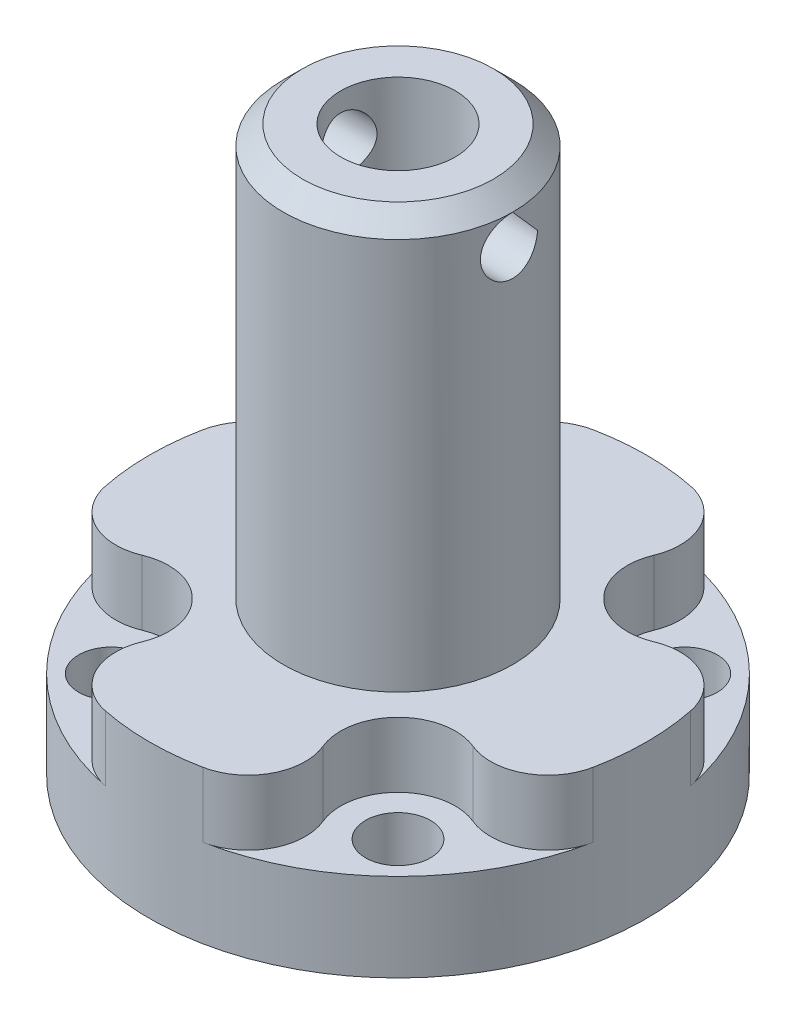
SolidWorks part; units mm, degrees
material "6061 Alloy"
ref_plane "Front Plane" through (0, 0, 0) normal (0, 0, 1) x (1, 0, 0)
ref_plane "Top Plane" through (0, 0, 0) normal (0, 1, 0) x (1, 0, 0)
ref_plane "Right Plane" through (0, 0, 0) normal (1, 0, 0) x (0, 0, -1)
sketch "Sketch1" plane through (0, 0, 0) normal (0, 1, 0) x (1, 0, 0)
  circle A0 centre (0, 0) radius 6
  dimension "D1" = 12
extrude "Boss-Extrude1" add sketch "Sketch1" along normal blind 29.5
sketch "Sketch3" plane through (0, 0, 0) normal (0, -1, 0) x (1, 0, 0)
  circle A0 centre (0, 0) radius 13
  dimension "D1" = 26
extrude "Boss-Extrude2" add sketch "Sketch3" against normal blind 8
sketch "Sketch2" plane through (0, 0, 0) normal (0, -1, 0) x (1, 0, 0)
  circle A0 centre (0, 0) radius 3
  dimension "D1" = 6
extrude "Cut-Extrude1" cut sketch "Sketch2" against normal through all
hole_wizard "CBORE for M3 Hexagon socket head cap screws1" positions "Sketch4" profile "Sketch5" counterbore size "M3" standard "GB" end condition through all
sketch "Sketch4" plane through (0, 8, 0) normal (0, 1, 0) x (1, 0, 0)
  line L0 (-6.6, 0) -> (6.6, 0) construction
  line L1 (0, -6.6) -> (0, 6.6) construction
  point P0 (-7.5, 7.5)
  point P5 (-7.5, -7.5)
  point P8 (7.5, -7.5)
  point P9 (7.5, 7.5)
  dimension "D1" = 15
  dimension "D2" = 15
sketch "Sketch5" plane through (-7.5, 8, -7.5) normal (1, 0, 0) x (0, 0, 1)
  line L0 (0, 0) -> (0, 8)
  line L1 (0, 8) -> (1.7, 8)
  line L3 (1.7, 8) -> (1.7, 3.4)
  line L4 (1.7, 3.4) -> (3, 3.4)
  line L5 (3, 3.4) -> (3, 0)
  line L7 (3, 0) -> (0, 0)
  line L11 (0, -6.35) -> (0, 107.95) construction
  dimension "Thru Hole Dia." = 3.4
  dimension "Thru Hole Depth" = 8
  dimension "C'Bore Dia." = 6
  dimension "C'Bore Depth" = 3.4
fillet "Fillet1" radius 3 8 edges at (10.4951, 6.3, -7.6716) (7.6716, 6.3, -10.4951) (7.6716, 6.3, 10.4951) (10.4951, 6.3, 7.6716) (-10.4951, 6.3, 7.6716) (-7.6716, 6.3, 10.4951) (-7.6716, 6.3, -10.4951) (-10.4951, 6.3, -7.6716)
chamfer "Chamfer1" distance 1 angle 45 1 edges at (0, 29.5, 6)
sketch "Sketch6" plane through (0, 0, 0) normal (1, 0, 0) x (0, 0, -1)
  circle A0 centre (0, 27) radius 1.5
  dimension "D1" = 3
  dimension "D2" = 27
extrude "Cut-Extrude2" cut sketch "Sketch6" against normal through all both and the other way through all
